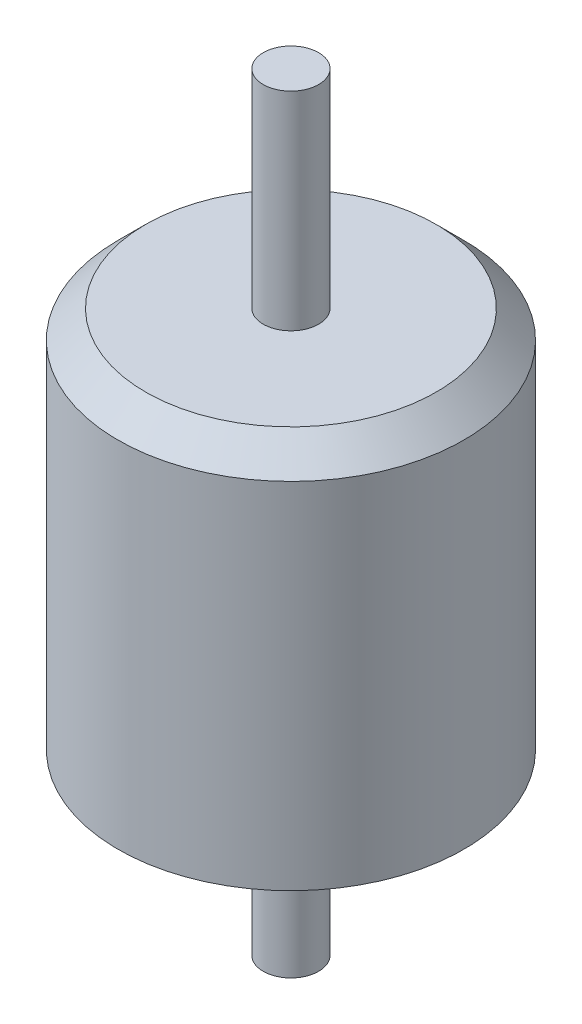
SolidWorks part; units mm, degrees
ref_plane "Front Plane" through (0, 0, 0) normal (0, 0, 1) x (1, 0, 0)
ref_plane "Top Plane" through (0, 0, 0) normal (0, 1, 0) x (1, 0, 0)
ref_plane "Right Plane" through (0, 0, 0) normal (1, 0, 0) x (0, 0, -1)
sketch "Sketch1" plane through (0, 0, 0) normal (0, 0, 1) x (1, 0, 0)
  line L0 (0, 0) -> (4, 0)
  line L1 (4, 0) -> (4, 16)
  line L2 (4, 16) -> (7, 16)
  line L3 (7, 16) -> (7, 20)
  line L4 (7, 20) -> (15, 20)
  line L5 (15, 20) -> (25, 25.7735)
  line L6 (25, 25.7735) -> (25, 77)
  line L7 (25, 77) -> (21, 81)
  line L8 (21, 81) -> (4, 81)
  line L9 (4, 81) -> (4, 111)
  line L10 (4, 111) -> (0, 111)
  line L11 (0, 111) -> (0, 0)
  point P11 (18.9963, 81)
  point P14 (25, 77.7704)
  dimension "D1" = 65
  dimension "D2" = 4
  dimension "D3" = 4
  dimension "D4" = 30
  dimension "D5" = 16
  dimension "D6" = 7
  dimension "D7" = 15
  dimension "D8" = 25
  dimension "D9" = 4
  dimension "D10" = 45
  dimension "D11" = 30
  dimension "D12" = 4
revolve "Revolve1" add sketch "Sketch1" angle 360 about L11
